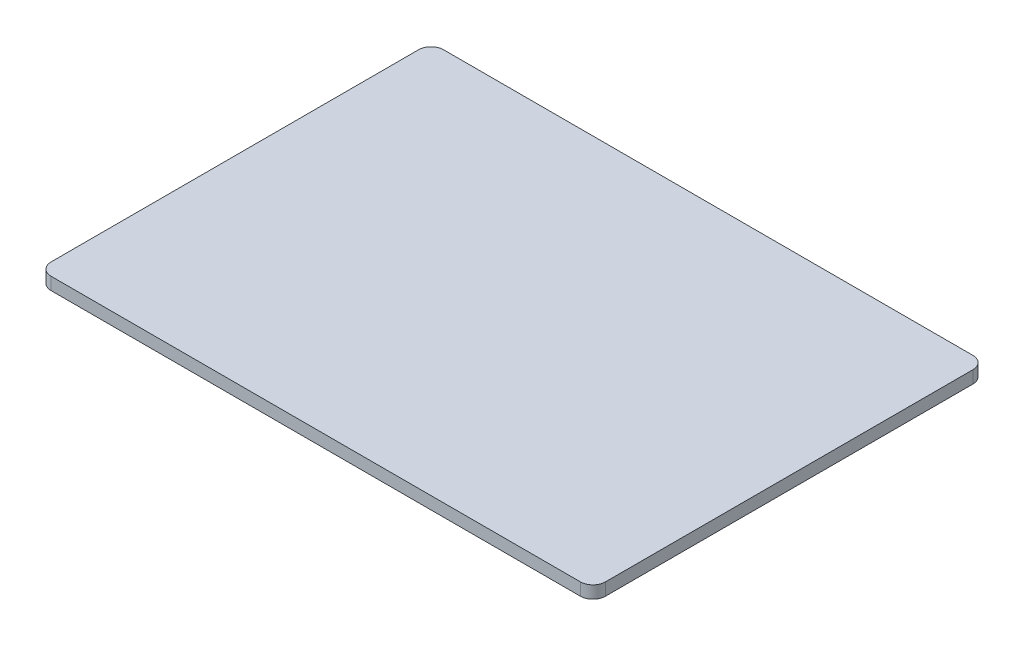
SolidWorks part; units mm, degrees
ref_plane "Front Plane" through (0, 0, 0) normal (0, 0, 1) x (1, 0, 0)
ref_plane "Top Plane" through (0, 0, 0) normal (0, 1, 0) x (1, 0, 0)
ref_plane "Right Plane" through (0, 0, 0) normal (1, 0, 0) x (0, 0, -1)
sketch "Sketch1" plane through (0, 0, 0) normal (0, 1, 0) x (1, 0, 0)
  line L1 (2.54, 0) -> (110.46, 0)
  line L2 (0, 2.54) -> (0, 77.46)
  line L3 (2.54, 80) -> (110.46, 80)
  line L4 (113, 2.54) -> (113, 77.46)
  arc A0 (110.46, 80) -> (113, 77.46) centre (110.46, 77.46) cw
  arc A1 (110.46, 0) -> (113, 2.54) centre (110.46, 2.54) ccw
  arc A2 (2.54, 0) -> (0, 2.54) centre (2.54, 2.54) cw
  arc A3 (0, 77.46) -> (2.54, 80) centre (2.54, 77.46) cw
  point P7 (113, 80)
  point P12 (0, 0)
  point P15 (0, 80)
  dimension "D3" = 2.54
  dimension "D1" = 80
  dimension "D2" = 113
extrude "Boss-Extrude1" add sketch "Sketch1" along normal blind 2.54
